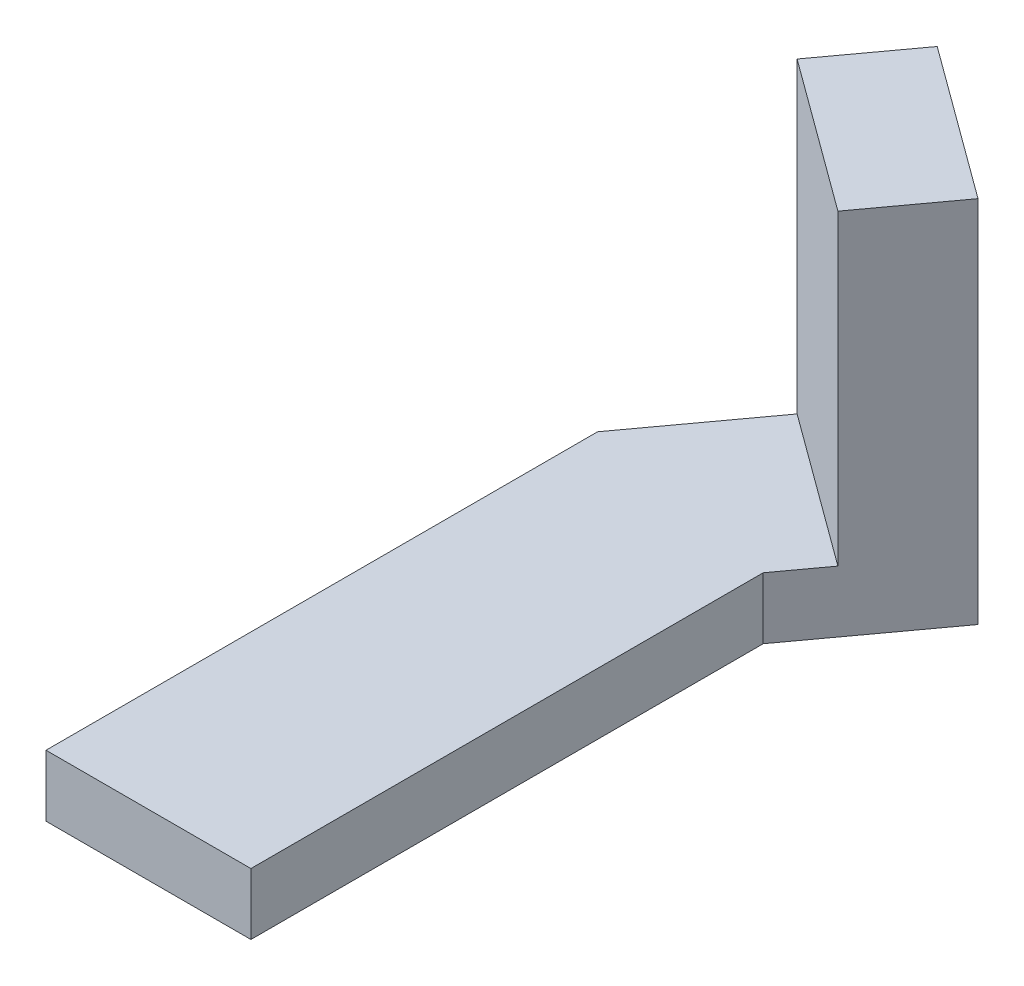
SolidWorks part; units mm, degrees
ref_plane "Front Plane" through (0, 0, 0) normal (0, 0, 1) x (1, 0, 0)
ref_plane "Top Plane" through (0, 0, 0) normal (0, 1, 0) x (1, 0, 0)
ref_plane "Right Plane" through (0, 0, 0) normal (1, 0, 0) x (0, 0, -1)
sketch "Sketch1" plane through (0, 0, 0) normal (0, 1, 0) x (1, 0, 0)
  line L0 (0, 0) -> (20, 0)
  line L1 (20, 0) -> (20, 50)
  line L2 (20, 50) -> (28.859, 62.1044)
  line L3 (28.859, 62.1044) -> (14.0083, 72.9734)
  line L4 (14.0083, 72.9734) -> (0, 53.8334)
  line L5 (0, 53.8334) -> (0, 0)
  dimension "D1" = 20
  dimension "D2" = 50
  dimension "D3" = 15
  dimension "D4" = 15
extrude "Boss-Extrude1" add sketch "Sketch1" along normal blind 6
sketch "Sketch2" plane through (0, 6, 0) normal (0, 1, 0) x (1, 0, 0)
  line L0 (14.0083, 72.9734) -> (8.2297, 65.0779)
  line L1 (14.0083, 72.9734) -> (0, 53.8334) construction
  line L2 (8.2297, 65.0779) -> (23.0804, 54.2089)
  line L3 (20, 50) -> (28.859, 62.1044) construction
  line L4 (23.0804, 54.2089) -> (28.859, 62.1044)
  line L5 (28.859, 62.1044) -> (14.0083, 72.9734)
extrude "Boss-Extrude2" add sketch "Sketch2" along normal blind 30
